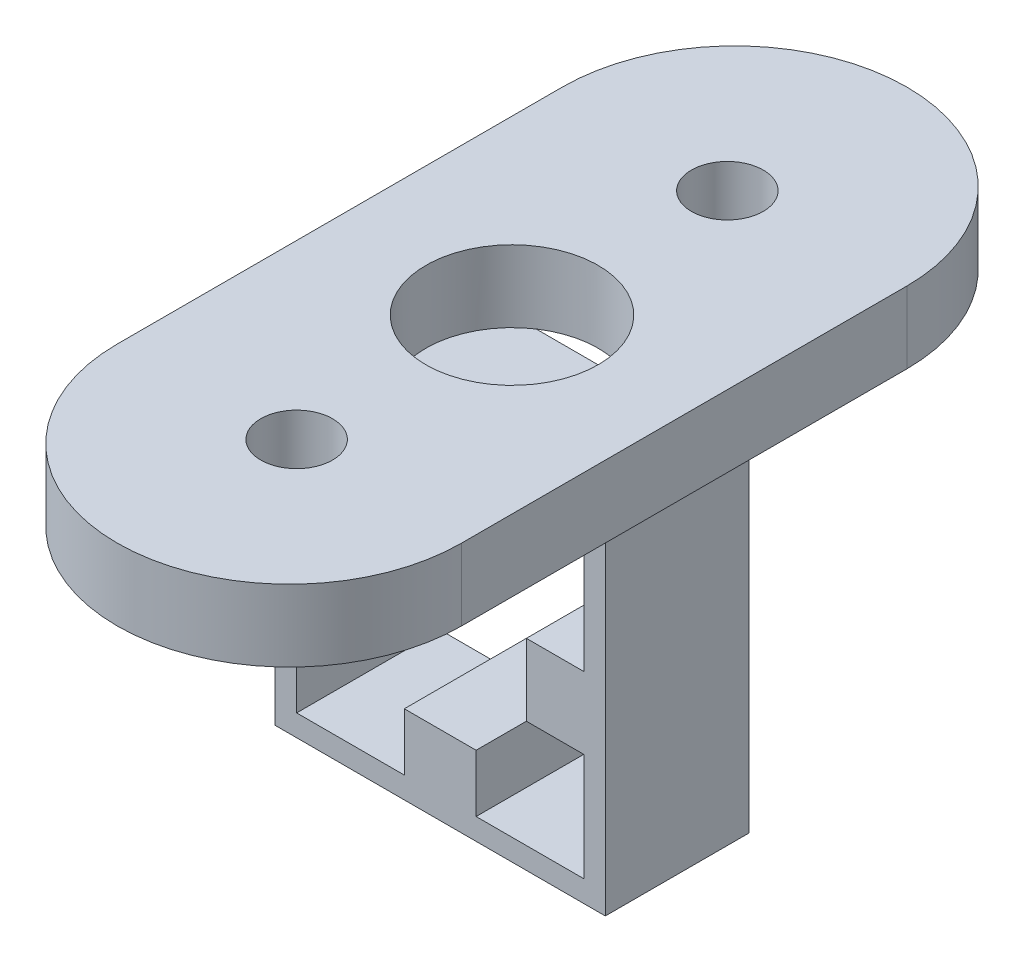
SolidWorks part; units mm, degrees
ref_plane "Front Plane" through (0, 0, 0) normal (0, 0, 1) x (1, 0, 0)
ref_plane "Top Plane" through (0, 0, 0) normal (0, 1, 0) x (1, 0, 0)
ref_plane "Right Plane" through (0, 0, 0) normal (1, 0, 0) x (0, 0, -1)
sketch "Sketch1" plane through (0, 0, 0) normal (0, 0, 1) x (1, 0, 0)
  line L0 (-2.5, 10) -> (-10, 10)
  line L1 (10, -10) -> (2.5, -10)
  line L2 (10, -10) -> (10, -2.5)
  line L3 (10, 10) -> (2.5, 10)
  line L4 (-10, -10) -> (-10, -2.5)
  line L7 (11.5, -11.5) -> (-11.5, -11.5)
  line L8 (11.5, -11.5) -> (11.5, 11.5)
  line L9 (11.5, 11.5) -> (-11.5, 11.5)
  line L10 (-11.5, -11.5) -> (-11.5, 11.5)
  line L14 (-2.5, 10) -> (-2.5, 6)
  line L15 (-2.5, 6) -> (2.5, 6)
  line L16 (2.5, 10) -> (2.5, 6)
  line L17 (6, 2.5) -> (6, -2.5)
  line L18 (10, 2.5) -> (6, 2.5)
  line L19 (10, -2.5) -> (6, -2.5)
  line L20 (2.5, -6) -> (-2.5, -6)
  line L21 (2.5, -10) -> (2.5, -6)
  line L22 (-2.5, -10) -> (-2.5, -6)
  line L23 (-6, -2.5) -> (-6, 2.5)
  line L24 (-10, -2.5) -> (-6, -2.5)
  line L25 (-10, 2.5) -> (-6, 2.5)
  line L26 (-10, 2.5) -> (-10, 10)
  line L27 (10, 2.5) -> (10, 10)
  line L28 (-2.5, -10) -> (-10, -10)
  point P0 (0, 0)
  point P6 (0, 0)
  dimension "D1" = 20
  dimension "D2" = 20
  dimension "D3" = 1.5
  dimension "D4" = 1.5
  dimension "D5" = 5
extrude "Boss-Extrude1" add sketch "Sketch1" along normal blind 10
sketch "Sketch2" plane through (0, 11.5, 0) normal (0, 1, 0) x (1, 0, 0)
  line L0 (-11.5, 0) -> (11.5, -10) construction
  line L1 (11.5, -10) -> (-11.5, -10) construction
  line L2 (11.5, -10) -> (11.5, 0) construction
  line L3 (-11.5, -10) -> (11.5, 0) construction
  line L4 (0, -20.5063) -> (0, 10.5063) construction
  line L5 (-12, -20.5063) -> (-12, 10.5063)
  line L6 (12, -20.5063) -> (12, 10.5063)
  line L7 (-11.5, -5) -> (12, -5) construction
  line L8 (-11.5, -10) -> (-11.5, 0) construction
  arc A2 (-12, -20.5063) -> (12, -20.5063) centre (0, -20.5063) ccw
  arc A3 (12, 10.5063) -> (-12, 10.5063) centre (0, 10.5063) ccw
  circle A4 centre (0, 10) radius 2.5
  circle A5 centre (0, -20) radius 2.5
  circle A6 centre (0, -5) radius 6
  point P11 (0, -5)
  dimension "D1" = 12
  dimension "D2" = 15
extrude "Boss-Extrude2" add sketch "Sketch2" along normal blind 5
